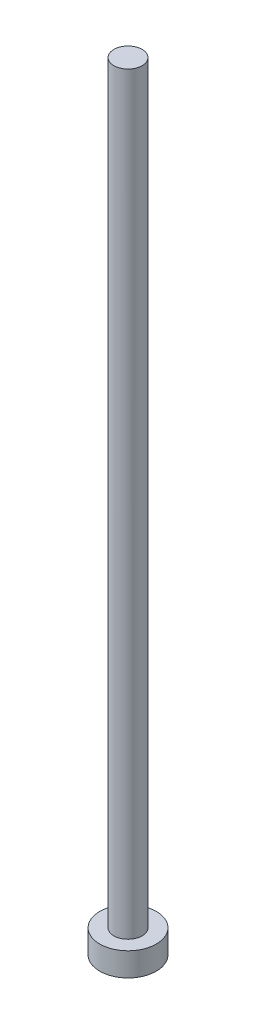
SolidWorks part; units mm, degrees
material "AISI 1020 Steel, Cold Rolled"
ref_plane "Front Plane" through (0, 0, 0) normal (0, 0, 1) x (1, 0, 0)
ref_plane "Top Plane" through (0, 0, 0) normal (0, 1, 0) x (1, 0, 0)
ref_plane "Right Plane" through (0, 0, 0) normal (1, 0, 0) x (0, 0, -1)
sketch "Sketch1" plane through (0, 0, 0) normal (0, 1, 0) x (1, 0, 0)
  circle A0 centre (0, 0) radius 3
  dimension "D1" = 6
extrude "Boss-Extrude1" add sketch "Sketch1" along normal blind 160
sketch "Sketch2" plane through (0, 0, 0) normal (0, -1, 0) x (1, 0, 0)
  circle A0 centre (0, 0) radius 6
  dimension "D1" = 12
extrude "Boss-Extrude2" add sketch "Sketch2" along normal blind 5
